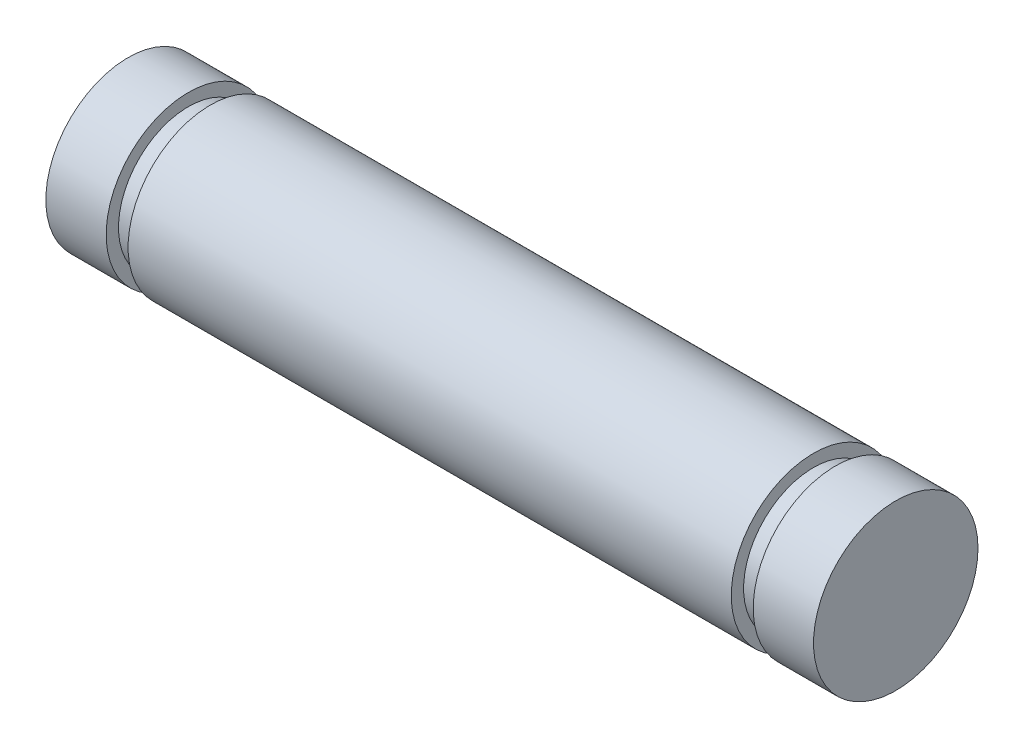
SolidWorks part; units mm, degrees
ref_plane "Alzado" through (0, 0, 0) normal (1, 0, 0) x (0, 1, 0)
ref_plane "Planta" through (0, 0, 0) normal (0, 0, 1) x (0, 1, 0)
ref_plane "Vista lateral" through (0, 0, 0) normal (0, 1, 0) x (-1, 0, 0)
sketch "Croquis1" plane through (0, 0, 0) normal (0, 1, 0) x (-1, 0, 0)
  line L1 (-11, 3) -> (11, 3)
  line L6 (14, 3) -> (14, 0)
  line L7 (-14, 0) -> (14, 0) construction
  line L22 (-14, 0) -> (14, 0)
  line L23 (11, 3) -> (11, 2.55)
  line L24 (11, 2.55) -> (11.8, 2.55)
  line L25 (11.8, 2.55) -> (11.8, 3)
  line L26 (11.8, 3) -> (14, 3)
  line L27 (0, 0) -> (0, 3) construction
  line L28 (-11.8, 3) -> (-14, 3)
  line L29 (-11.8, 2.55) -> (-11.8, 3)
  line L30 (-11, 2.55) -> (-11.8, 2.55)
  line L31 (-11, 3) -> (-11, 2.55)
  line L32 (-14, 3) -> (-14, 0)
  dimension "D1" = 28
  dimension "D2" = 6
  dimension "D3" = 22
  dimension "D5" = 0.8
  dimension "D7" = 0.45
revolve "Revolución1" add sketch "Croquis1" angle 360 about L7
equation "\"ancho_circlip\"=0.8"
equation "\"ranura_circlip\"=0.45"
